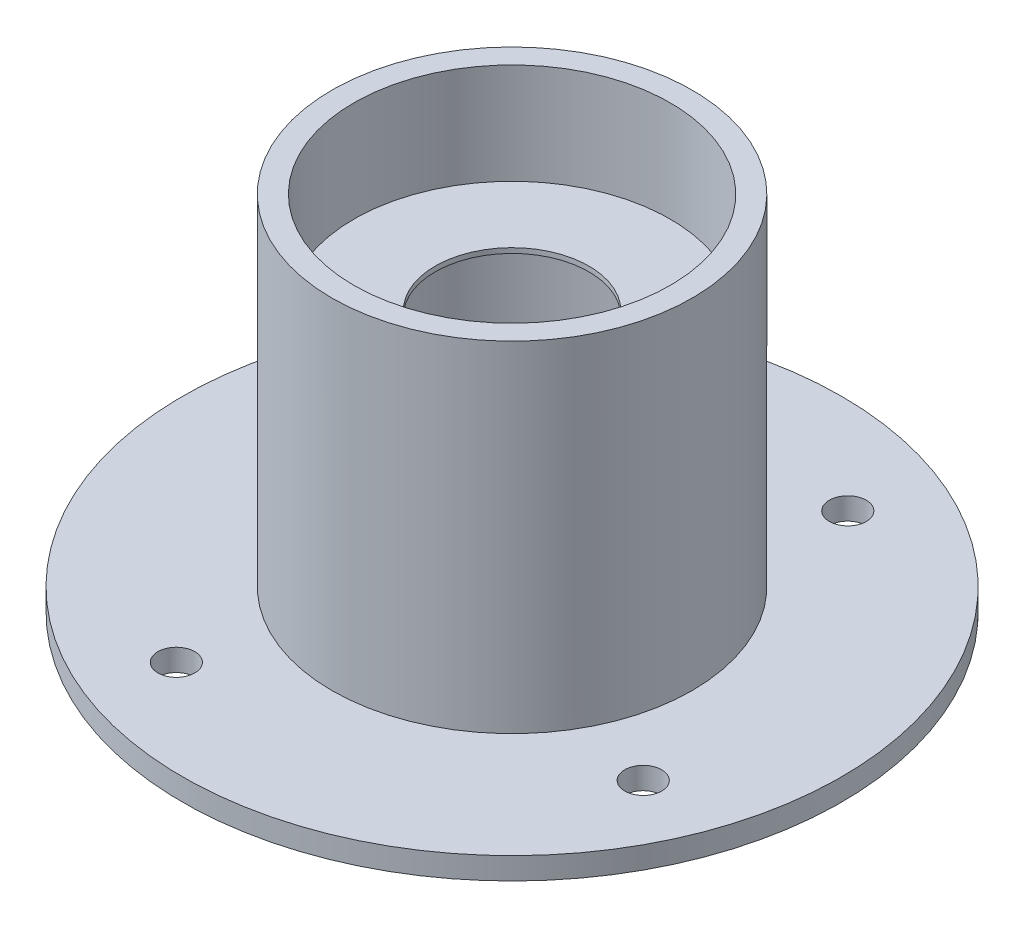
SolidWorks part; units mm, degrees
ref_plane "Plan de face" through (0, 0, 0) normal (0, 0, 1) x (1, 0, 0)
ref_plane "Plan de dessus" through (0, 0, 0) normal (0, 1, 0) x (1, 0, 0)
ref_plane "Plan de droite" through (0, 0, 0) normal (1, 0, 0) x (0, 0, -1)
sketch "Esquisse1" plane through (0, 0, 0) normal (0, 0, 1) x (1, 0, 0)
  line L0 (-17.5, 0.57) -> (-17.5, -0.57)
  line L1 (-17.5, -0.57) -> (-36, -0.57)
  line L2 (-36, -0.57) -> (-36, -50)
  line L3 (-36, -50) -> (-41, -50)
  line L4 (-41, -50) -> (-41, 50)
  line L5 (-41, 50) -> (-36, 50)
  line L6 (-36, 50) -> (-36, 0.57)
  line L7 (-36, 0.57) -> (-17.5, 0.57)
  line L8 (0, 7.7111) -> (0, -6.9519) construction
  line L9 (-11.1378, 0) -> (10.282, 0) construction
  dimension "D1" = 35
  dimension "D2" = 72
  dimension "D3" = 5
  dimension "D4" = 100
  dimension "D5" = 1.14
revolve "Révolution1" add sketch "Esquisse1" angle 360 about L8
sketch "Esquisse2" plane through (0, -50, 0) normal (0, -1, 0) x (1, 0, 0)
  circle A0 centre (0, 0) radius 36 construction
  circle A1 centre (0, 0) radius 41
  circle A2 centre (0, 0) radius 41
  circle A3 centre (0, 0) radius 36
  dimension "D1" = 0
extrude "Boss.-Extru.1" add sketch "Esquisse2" along normal blind 3.85
sketch "Esquisse4" plane through (0, 50, 0) normal (0, 1, 0) x (1, 0, 0)
  circle A0 centre (0, 0) radius 41 construction
  circle A1 centre (0, 0) radius 36 construction
  circle A2 centre (0, 0) radius 41
  circle A3 centre (0, 0) radius 36
extrude "Enlèv. mat.-Extru.2" cut sketch "Esquisse4" against normal blind 26.5
sketch "Esquisse5" plane through (0, -53.85, 0) normal (0, -1, 0) x (1, 0, 0)
  circle A0 centre (0, 0) radius 75
  circle A3 centre (0, 0) radius 36 construction
  circle A4 centre (0, 0) radius 36
  dimension "D1" = 150
extrude "Boss.-Extru.2" add sketch "Esquisse5" along normal blind 5
hole_wizard "Dégagement M81" positions "Esquisse7" profile "Esquisse8" hole size "M8" standard "DIN" end condition through all
sketch "Esquisse7" plane through (0, -53.85, 0) normal (0, 1, 0) x (1, 0, 0)
  circle A1 centre (0, 0) radius 36 construction
  point P0 (53.124, -23.2775)
  dimension "D1" = 58
sketch "Esquisse8" plane through (53.124, -53.85, 23.2775) normal (1, 0, 0) x (0, 0, 1)
  line L0 (0, 0) -> (0, 5)
  line L1 (0, 5) -> (4.2, 5)
  line L2 (4.2, 5) -> (4.2, 0)
  line L5 (4.2, 0) -> (0, 0)
  line L11 (0, -6.35) -> (0, 107.95) construction
  dimension "Diamètre du perçage jusqu'au prochain" = 8.4
  dimension "Profondeur du perçage jusqu'au prochain" = 5
pattern_circular "Répétition circulaire1" count 4 every 90 about axis through (0, 0, 0) along (0, 1, 0) of "Dégagement M81"
